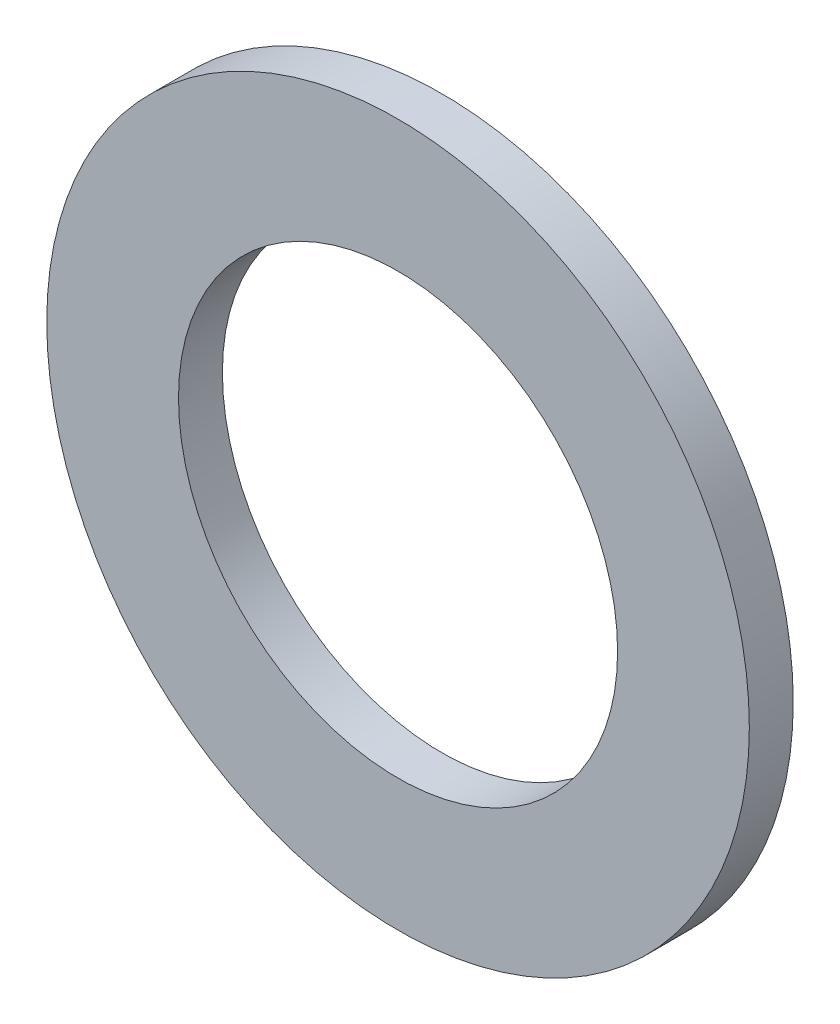
SolidWorks part; units mm, degrees
ref_plane "前视基准面" through (0, 0, 0) normal (0, 0, 1) x (1, 0, 0)
ref_plane "上视基准面" through (0, 0, 0) normal (0, 1, 0) x (1, 0, 0)
ref_plane "右视基准面" through (0, 0, 0) normal (1, 0, 0) x (0, 0, -1)
sketch "草图1" plane through (0, 0, 0) normal (0, 0, 1) x (1, 0, 0)
  circle A0 centre (0, 0) radius 5
  circle A1 centre (0, 0) radius 8
extrude "凸台-拉伸1" add sketch "草图1" along normal blind 1
